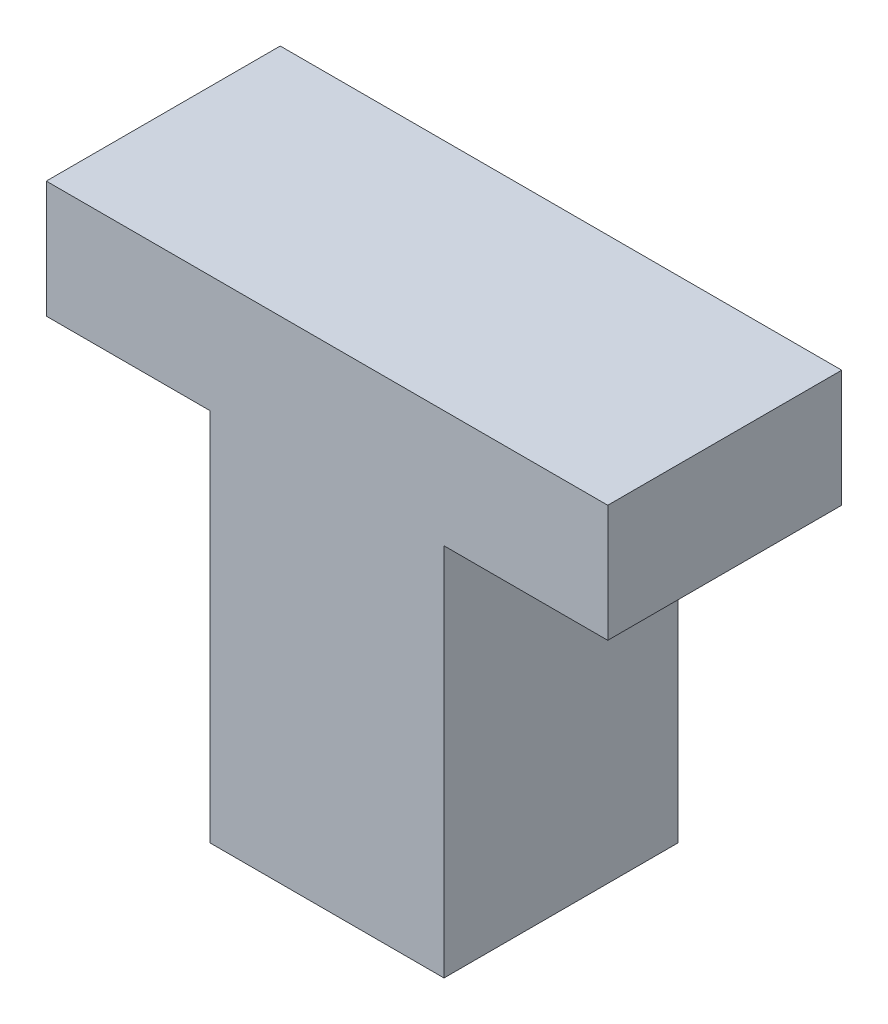
SolidWorks part; units mm, degrees
ref_plane "Front Plane" through (0, 0, 0) normal (0, 0, 1) x (1, 0, 0)
ref_plane "Top Plane" through (0, 0, 0) normal (0, 1, 0) x (1, 0, 0)
ref_plane "Right Plane" through (0, 0, 0) normal (1, 0, 0) x (0, 0, -1)
sketch "Sketch1" plane through (0, 0, 0) normal (0, 0, 1) x (1, 0, 0)
  line L0 (-2.5, 0) -> (2.5, 0)
  line L1 (2.5, 0) -> (2.5, 8)
  line L2 (2.5, 8) -> (6, 8)
  line L3 (6, 8) -> (6, 10.5)
  line L4 (6, 10.5) -> (-6, 10.5)
  line L5 (-6, 10.5) -> (-6, 8)
  line L6 (-6, 8) -> (-2.5, 8)
  line L7 (-2.5, 8) -> (-2.5, 0)
  point P3 (0, 0)
  point P10 (0, 10.5)
  dimension "D1" = 2.5
  dimension "D2" = 12
  dimension "D3" = 3.5
  dimension "D4" = 10.5
extrude "Boss-Extrude1" add sketch "Sketch1" along normal mid plane 5
